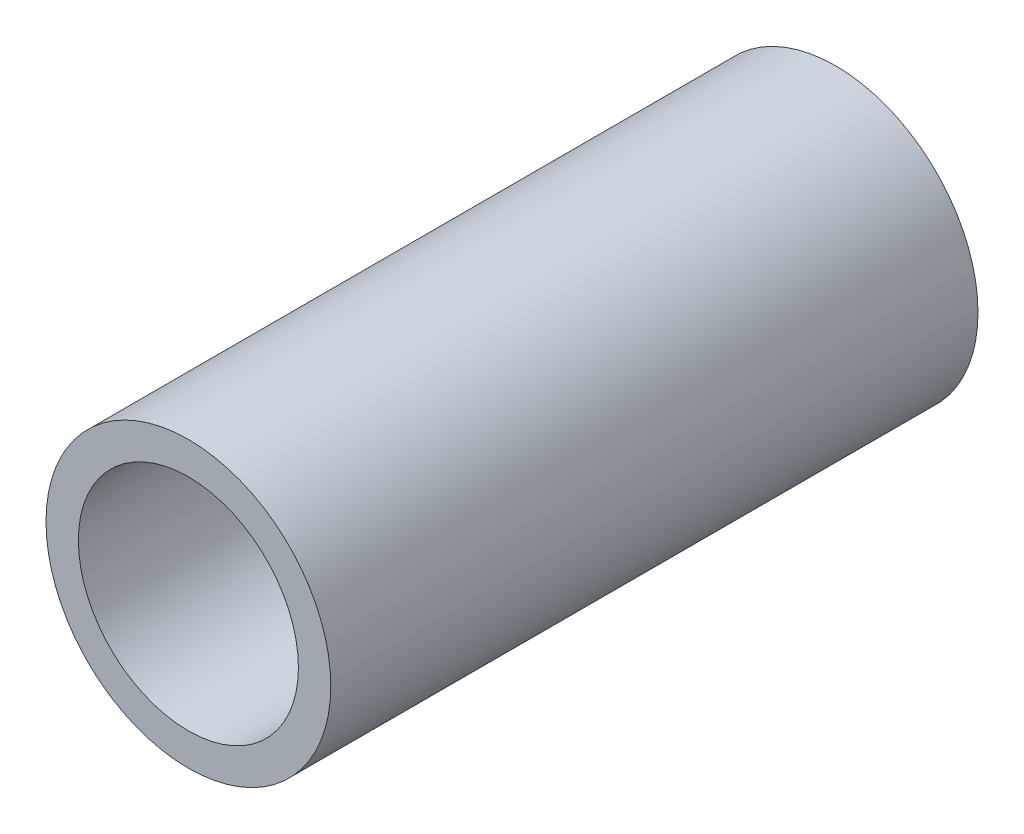
SolidWorks part; units mm, degrees
ref_plane "Front Plane" through (0, 0, 0) normal (0, 0, 1) x (1, 0, 0)
ref_plane "Top Plane" through (0, 0, 0) normal (0, 1, 0) x (1, 0, 0)
ref_plane "Right Plane" through (0, 0, 0) normal (1, 0, 0) x (0, 0, -1)
sketch "Sketch1" plane through (0, 0, 0) normal (0, 0, 1) x (1, 0, 0)
  circle A0 centre (0, 0) radius 1.7
  circle A1 centre (0, 0) radius 2.2
  dimension "D1" = 3.4
  dimension "D2" = 4.4
extrude "Boss-Extrude1" add sketch "Sketch1" along normal blind 10
